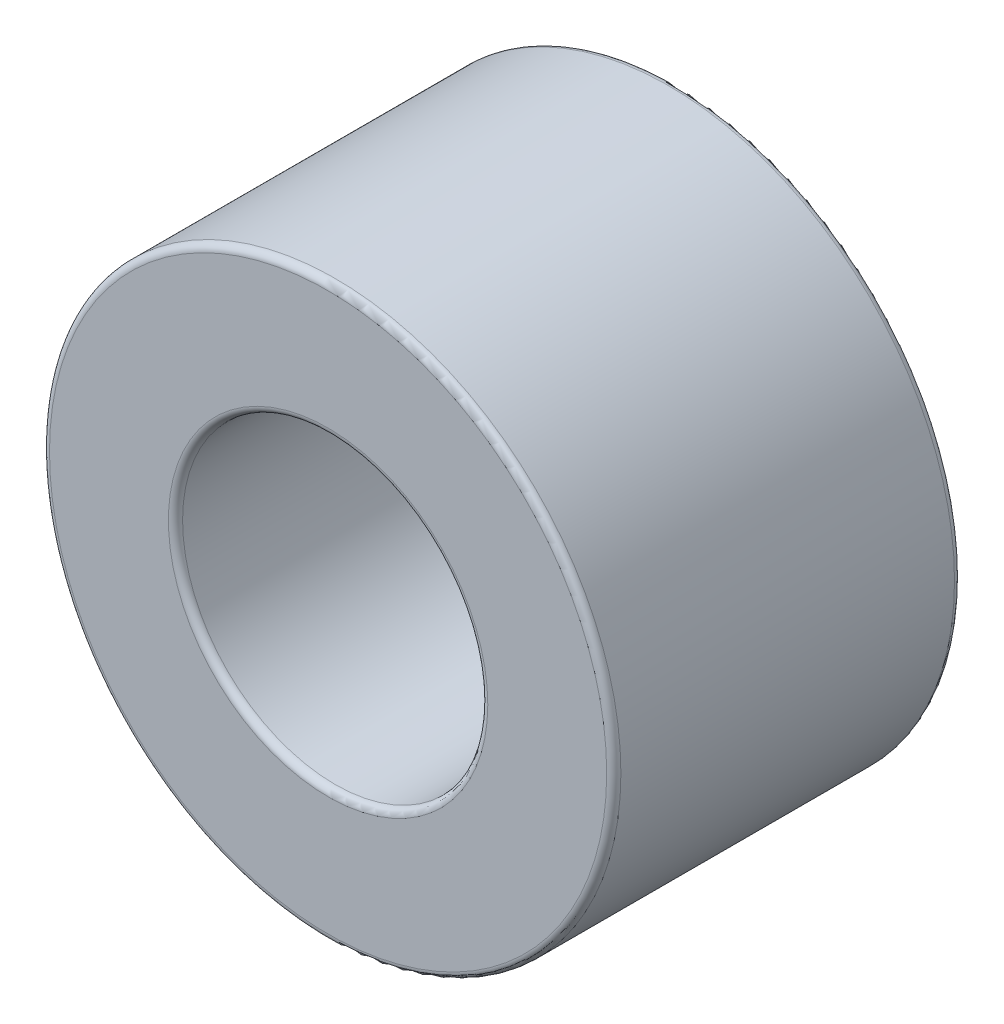
SolidWorks part; units mm, degrees
material "Nylon 101"
ref_plane "Front Plane" through (0, 0, 0) normal (0, 0, 1) x (1, 0, 0)
ref_plane "Top Plane" through (0, 0, 0) normal (0, 1, 0) x (1, 0, 0)
ref_plane "Right Plane" through (0, 0, 0) normal (1, 0, 0) x (0, 0, -1)
sketch "Sketch1" plane through (0, 0, 0) normal (0, 0, 1) x (1, 0, 0)
  circle A0 centre (0, 0) radius 10.2235
  circle A1 centre (0, 0) radius 5.461
  dimension "D1" = 10.922
  dimension "D2" = 4.7625
extrude "Boss-Extrude1" add sketch "Sketch1" along normal blind 12.446
fillet "Fillet2" radius 0.254 4 edges at (5.461, 0, 0) (10.2235, 0, 0) (5.461, 0, 12.446) (10.2235, 0, 12.446)
